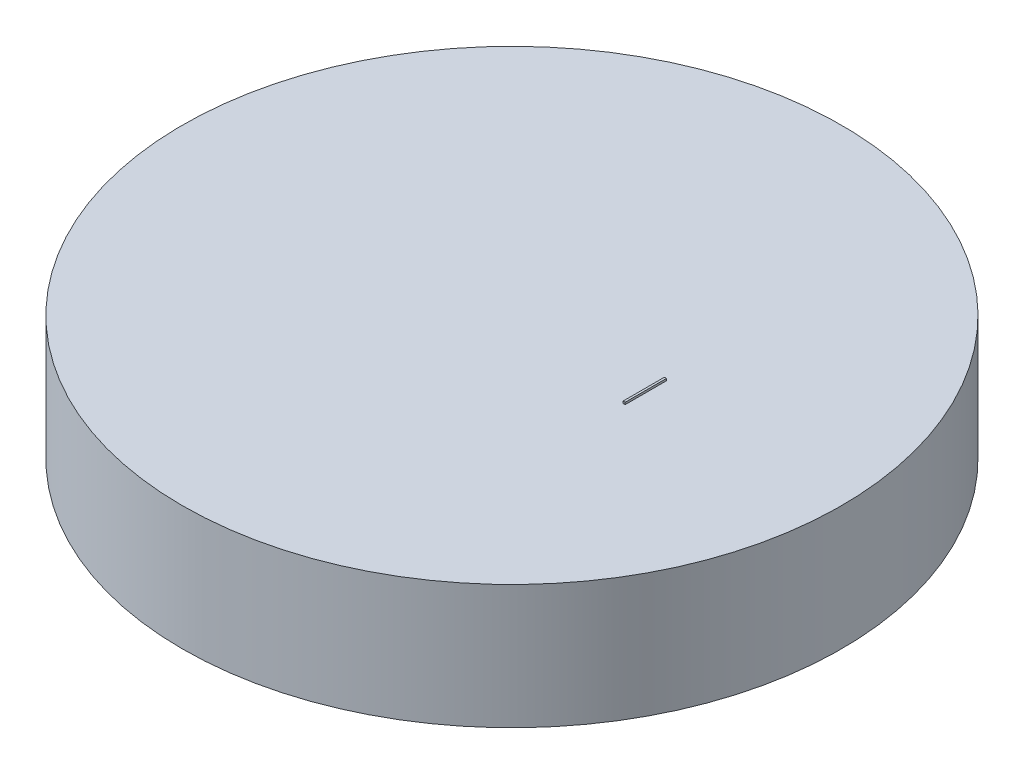
SolidWorks part; units mm, degrees
ref_plane "Front Plane" through (0, 0, 0) normal (0, 0, 1) x (1, 0, 0)
ref_plane "Top Plane" through (0, 0, 0) normal (0, 1, 0) x (1, 0, 0)
ref_plane "Right Plane" through (0, 0, 0) normal (1, 0, 0) x (0, 0, -1)
sketch "Sketch1" plane through (0, 0, 0) normal (0, 1, 0) x (1, 0, 0)
  circle A0 centre (0, 0) radius 159.375
extrude "Boss-Extrude2" add sketch "Sketch1" along normal blind 60 contours A0
sketch "Sketch3" plane through (0, 60, 0) normal (0, 1, 0) x (1, 0, 0)
  line L0 (0, 0) -> (63.75, 0)
  line L1 (63.75, 0) -> (63.75, -9.9904)
  line L3 (64.75, -9.9904) -> (64.75, 9.9904)
  line L4 (64.75, 9.9904) -> (63.75, 9.9904)
  line L5 (63.75, -9.9904) -> (64.75, -9.9904)
  line L6 (63.75, 0) -> (63.75, 9.9904)
extrude "Boss-Extrude4" add sketch "Sketch3" along normal blind 1
